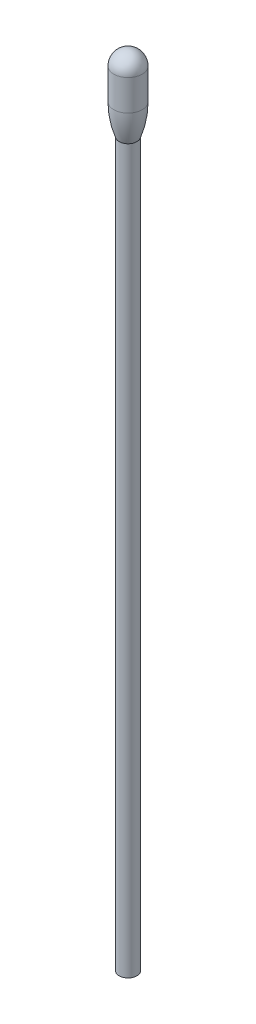
SolidWorks part; units mm, degrees
ref_plane "Front" through (0, 0, 0) normal (0, 0, 1) x (1, 0, 0)
ref_plane "Top" through (0, 0, 0) normal (0, 1, 0) x (1, 0, 0)
ref_plane "Right" through (0, 0, 0) normal (1, 0, 0) x (0, 0, -1)
sketch "Esquisse1" plane through (0, 0, 0) normal (0, 0, 1) x (1, 0, 0)
  line L0 (0, -0.0532) -> (0, 141.4181) construction
  line L1 (-0.625, 0) -> (-0.625, 132.9222)
  line L2 (-0.625, 132.9222) -> (0, 132.9222)
  line L3 (0, 132.9222) -> (0, 135)
  line L4 (0, 135) -> (-0.0016, 135)
  line L5 (-2.4016, 132.5984) -> (-2.4016, 127.3869)
  line L6 (-1.5, 122.2545) -> (-1.5, 0)
  line L7 (-1.5, 0) -> (-0.625, 0)
  arc A0 (0, 135) -> (-2.4016, 132.5984) centre (0, 132.5984) ccw
  arc A1 (-2.4016, 127.3869) -> (-1.5, 122.2545) centre (12.6565, 127.3869) ccw
  dimension "D1" = 135
  dimension "D2" = 3
  dimension "D3" = 1.25
revolve "Révolution3" add sketch "Esquisse1" angle 360 about L0
